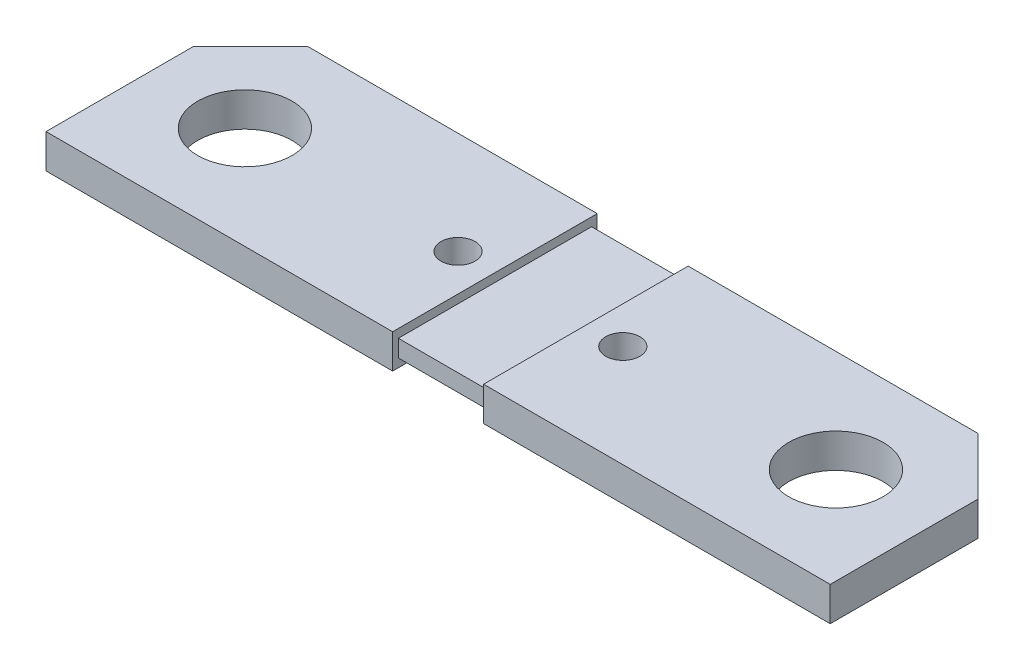
SolidWorks part; units mm, degrees
ref_plane "Front Plane" through (0, 0, 0) normal (0, 0, 1) x (1, 0, 0)
ref_plane "Top Plane" through (0, 0, 0) normal (0, 1, 0) x (1, 0, 0)
ref_plane "Right Plane" through (0, 0, 0) normal (1, 0, 0) x (0, 0, -1)
sketch "Sketch1" plane through (0, 0, 0) normal (0, 1, 0) x (1, 0, 0)
  line L0 (-4, -9) -> (-34.5, -9)
  line L1 (-34.5, -9) -> (-34.5, 4)
  line L2 (-34.5, 4) -> (-29.5, 9)
  line L3 (-29.5, 9) -> (-4, 9)
  line L4 (-4, 9) -> (-4, -9)
  line L5 (0, -9) -> (0, 9) construction
  line L6 (4, 9) -> (4, -9)
  line L7 (29.5, 9) -> (4, 9)
  line L8 (34.5, 4) -> (29.5, 9)
  line L9 (34.5, -9) -> (34.5, 4)
  line L10 (4, -9) -> (34.5, -9)
  circle A0 centre (-26, 0) radius 4.15
  circle A1 centre (-7.25, 0) radius 1.5
  circle A2 centre (7.25, 0) radius 1.5
  circle A3 centre (26, 0) radius 4.15
  point P2 (-4, 0)
  point P10 (0, 0)
  point P19 (0, 0)
  dimension "D4" = 52
  dimension "D5" = 8.3
  dimension "D6" = 3
  dimension "D7" = 14.5
  dimension "D1" = 18
  dimension "D2" = 69
  dimension "D3" = 45
  dimension "D8" = 8
  dimension "D9" = 5
extrude "Boss-Extrude1" add sketch "Sketch1" along normal mid plane 3
sketch "Sketch2" plane through (0, 0, 0) normal (0, 1, 0) x (1, 0, 0)
  line L0 (4, 9) -> (4, -9) construction
  line L1 (-4, 8.5) -> (4, 8.5)
  line L2 (-4, 8.5) -> (-4, -8.5)
  line L3 (-4, -8.5) -> (4, -8.5)
  line L4 (4, 8.5) -> (4, -8.5)
  line L5 (-4, -9) -> (-4, 9) construction
  line L6 (-4, 9) -> (-29.5, 9) construction
  point P4 (4, -8.4052)
  point P9 (-4, 8.2595)
  point P14 (4, 0)
  dimension "D1" = 0.5
extrude "Boss-Extrude2" add sketch "Sketch2" along normal mid plane 1.5
